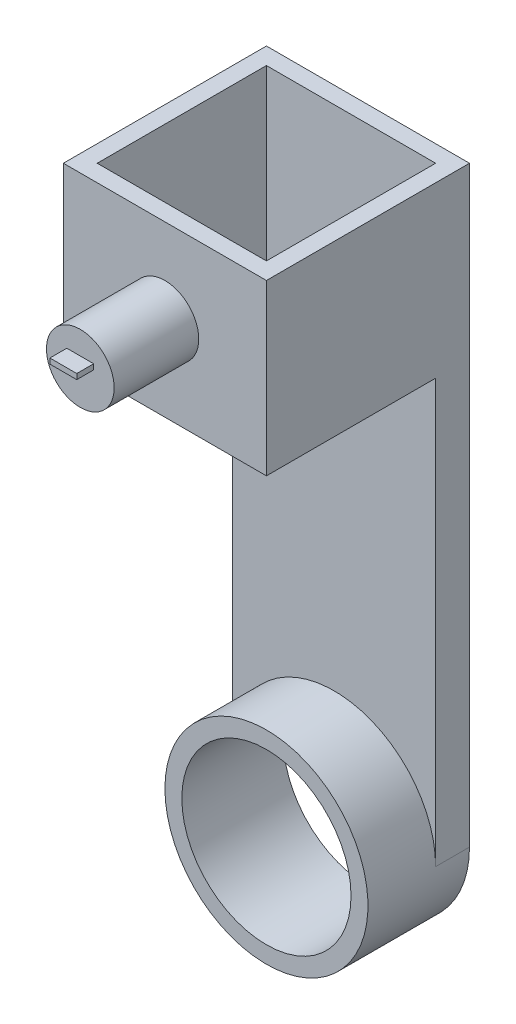
SolidWorks part; units mm, degrees
material "ABS"
ref_plane "前视基准面" through (0, 0, 0) normal (0, 0, 1) x (1, 0, 0)
ref_plane "上视基准面" through (0, 0, 0) normal (0, 1, 0) x (1, 0, 0)
ref_plane "右视基准面" through (0, 0, 0) normal (1, 0, 0) x (0, 0, -1)
other "Configuration Table"
sketch "草图1" plane through (0, 0, 0) normal (0, 0, 1) x (1, 0, 0)
  line L0 (-6, 0) -> (6, 0)
  line L1 (6, 0) -> (6, 25)
  line L2 (6, 25) -> (-6, 25)
  line L3 (-6, 25) -> (-6, 0)
  circle A0 centre (0, 0) radius 5
  circle A1 centre (0, 0) radius 6
extrude "凸台-拉伸1" add sketch "草图1" along normal blind 2 contours A1 L1 L2 L3
ref_plane "基准面1" through (6, 0, 0) normal (0, 1, 0) x (1, 0, 0)
ref_plane "基准面2" through (-6, 0, 0) normal (0, -1, 0) x (-1, 0, 0)
sketch "草图4" plane through (0, 0, 0) normal (0, 0, -1) x (-1, 0, 0)
  circle A0 centre (0, 0) radius 6
  circle A1 centre (0, 0) radius 5
extrude "凸台-拉伸2" add sketch "草图4" against normal blind 6
sketch "草图5" plane through (0, 25, 0) normal (0, 1, 0) x (1, 0, 0)
  line L1 (-6, 0) -> (6, 0)
  line L2 (-6, 0) -> (-6, -12)
  line L3 (-6, -12) -> (6, -12)
  line L4 (6, 0) -> (6, -12)
extrude "凸台-拉伸3" add sketch "草图5" along normal blind 10
sketch "草图6" plane through (0, 35, 0) normal (0, 1, 0) x (1, 0, 0)
  line L0 (-6, 0) -> (6, -12)
  line L1 (6, 0) -> (-6, 0) construction
  line L2 (-6, 0) -> (-6, -12) construction
  line L4 (-5, -11) -> (5, -11)
  line L5 (-5, -11) -> (-5, -1)
  line L6 (-5, -1) -> (5, -1)
  line L7 (5, -11) -> (5, -1)
  line L8 (-5, -11) -> (5, -1) construction
  line L9 (-5, -1) -> (5, -11) construction
  point P7 (0, -6)
extrude "切除-拉伸1" cut sketch "草图6" against normal blind 10 contours L0 L7 L6 | L5 L4 L0
sketch "草图7" plane through (0, 0, 12) normal (0, 0, 1) x (1, 0, 0)
  line L0 (-6, 35) -> (6, 25)
  circle A0 centre (0, 30) radius 2
extrude "凸台-拉伸4" add sketch "草图7" along normal blind 5 contours L0 A0 | L0 A0
sketch "草图9" plane through (0, 0, 17) normal (0, 0, 1) x (1, 0, 0)
  line L0 (-0.7972, 30.6335) -> (0.7913, 30.6335)
  line L1 (-0.7972, 30.6335) -> (-0.7972, 30.3197)
  line L2 (-0.7972, 30.3197) -> (0.7913, 30.3197)
  line L3 (0.7913, 30.3197) -> (0.7913, 30.6335)
extrude "凸台-拉伸6" add sketch "草图9" along normal blind 1
